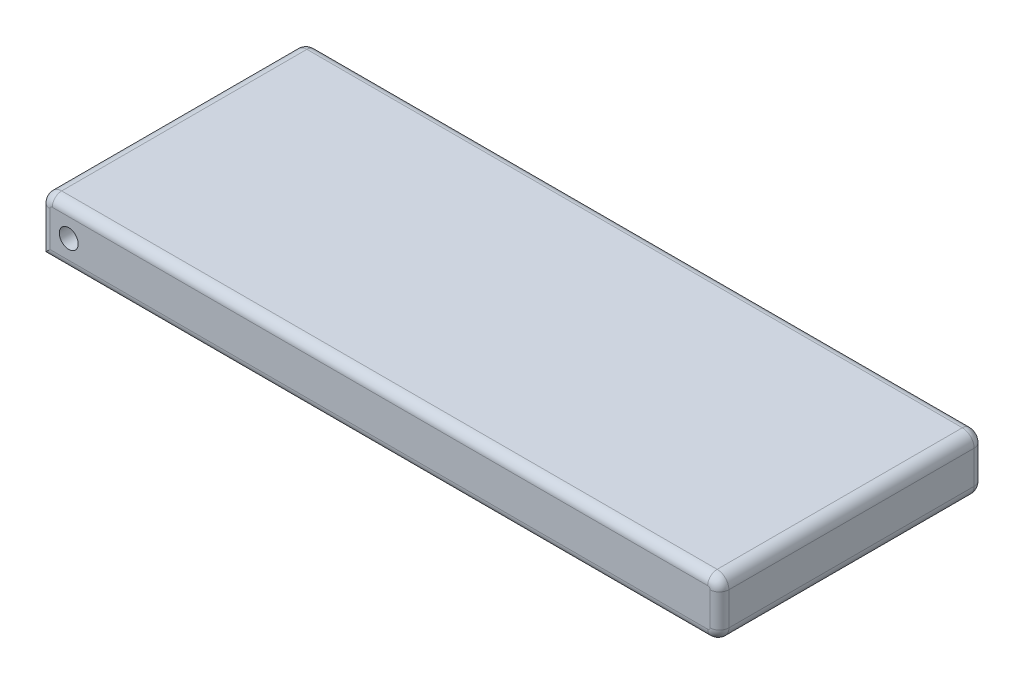
SolidWorks part; units mm, degrees
material "Hexcel AS4C (3000 Filaments)"
ref_plane "Front Plane" through (0, 0, 0) normal (0, 0, 1) x (1, 0, 0)
ref_plane "Top Plane" through (0, 0, 0) normal (0, 1, 0) x (1, 0, 0)
ref_plane "Right Plane" through (0, 0, 0) normal (1, 0, 0) x (0, 0, -1)
sketch "Sketch1" plane through (0, 0, 0) normal (0, 1, 0) x (1, 0, 0)
  line L1 (914.4, -355.6) -> (-914.4, -355.6)
  line L2 (914.4, -355.6) -> (914.4, 355.6)
  line L3 (914.4, 355.6) -> (-914.4, 355.6)
  line L4 (-914.4, -355.6) -> (-914.4, 355.6)
  line L5 (914.4, -355.6) -> (-914.4, 355.6) construction
  line L6 (914.4, 355.6) -> (-914.4, -355.6) construction
  point P0 (0, 0)
  dimension "D1" = 711.2
  dimension "D2" = 1828.8
extrude "Boss-Extrude1" add sketch "Sketch1" along normal blind 152.4
sketch "Sketch2" plane through (0, 0, 355.6) normal (0, 0, 1) x (1, 0, 0)
  line L0 (-914.4, 152.4) -> (-914.4, 0) construction
  circle A0 centre (-838.2, 76.2) radius 25.4
  point P5 (-914.4, 76.2)
  dimension "D1" = 50.8
  dimension "D2" = 76.2
extrude "Cut-Extrude1" cut sketch "Sketch2" against normal blind 818.642
fillet "Fillet1" radius 31.75 3 edges at (914.4, 152.4, 0) (914.4, 0, 0) (-914.4, 152.4, 0)
fillet "Fillet2" radius 25.4 14 edges at (-914.4, 60.325, -355.6) (0, 152.4, -355.6) (905.1006, 143.1006, -355.6) (914.4, 76.2, -355.6) (905.1006, 9.2994, -355.6) (-914.4, 60.325, 355.6) (0, 152.4, 355.6) (905.1006, 143.1006, 355.6) (914.4, 76.2, 355.6) (905.1006, 9.2994, 355.6) (-15.875, 0, -355.6) (-15.875, 0, 355.6) (-905.1006, 143.1006, -355.6) (-905.1006, 143.1006, 355.6)
sketch "Sketch3" plane through (0, 0, 0) normal (0, -1, 0) x (-1, 0, 0)
  text T0 "<b>NASA FLEXBED</b>" font "Century Gothic" height 127
extrude "Cut-Extrude2" cut sketch "Sketch3" against normal blind 5.08
scale "Scale1" scale about centroid uniform scaling yes scale factor 0.5867
